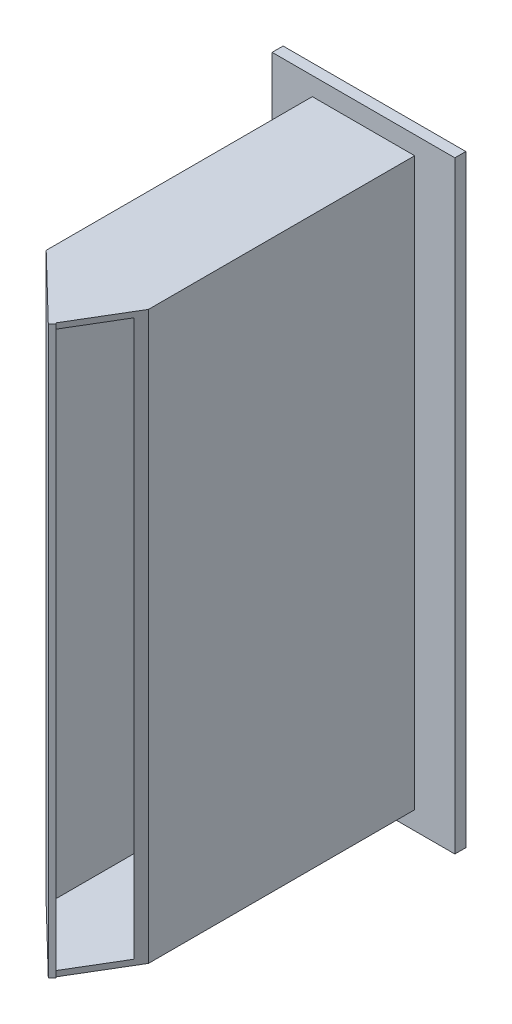
SolidWorks part; units mm, degrees
ref_plane "前视基准面" through (0, 0, 0) normal (0, 0, 1) x (1, 0, 0)
ref_plane "上视基准面" through (0, 0, 0) normal (0, 1, 0) x (1, 0, 0)
ref_plane "右视基准面" through (0, 0, 0) normal (1, 0, 0) x (0, 0, -1)
sketch "草图1" plane through (0, 0, 0) normal (0, 0, 1) x (1, 0, 0)
  line L0 (0, 16.5) -> (10, 16.5) construction
  line L1 (0, 0) -> (10, 0)
  line L2 (0, 0) -> (0, 33)
  line L3 (0, 33) -> (10, 33)
  line L4 (10, 0) -> (10, 33)
  line L5 (2.5, 31.7) -> (7.5, 31.7)
  line L6 (2.5, 31.7) -> (2.5, 1.3)
  line L7 (2.5, 1.3) -> (7.5, 1.3)
  line L8 (7.5, 31.7) -> (7.5, 1.3)
  line L9 (5, 33) -> (5, 0) construction
  dimension "D1" = 33
  dimension "D2" = 10
  dimension "D3" = 5
  dimension "D4" = 30.4
extrude "凸台-拉伸1" add sketch "草图1" along normal blind 0.6
sketch "草图2" plane through (0, 0, 0.6) normal (0, 0, 1) x (1, 0, 0)
  line L0 (7.5, 1.3) -> (7.5, 31.7) construction
  line L1 (2.2, 32) -> (7.8, 32)
  line L2 (2.2, 32) -> (2.2, 1)
  line L3 (2.2, 1) -> (7.8, 1)
  line L4 (7.8, 32) -> (7.8, 1)
  line L5 (2.5, 31.7) -> (2.5, 1.3) construction
  line L6 (7.5, 31.7) -> (2.5, 31.7) construction
  line L7 (2.5, 1.3) -> (7.5, 1.3) construction
  line L9 (2.5, 31.7) -> (7.5, 31.7)
  line L10 (2.5, 31.7) -> (2.5, 1.3)
  line L11 (2.5, 1.3) -> (7.5, 1.3)
  line L12 (7.5, 31.7) -> (7.5, 1.3)
  dimension "D1" = 0.3
  dimension "D2" = 0.3
  dimension "D3" = 0.3
  dimension "D4" = 0.3
extrude "凸台-拉伸2" add sketch "草图2" along normal blind 18
sketch "草图5" plane through (0, 32, 0) normal (0, 1, 0) x (1, 0, 0)
  line L0 (2.2, -15.1659) -> (5.749, -18.6)
  line L1 (2.2, -18.6) -> (2.2, -0.6) construction
  line L2 (7.8, -18.6) -> (2.2, -18.6) construction
  line L3 (5.749, -18.6) -> (7.8, -15.1659)
  line L4 (7.8, -18.6) -> (7.8, -0.6) construction
  line L5 (2.2, -15.1659) -> (2.2, -19.3766)
  line L6 (2.2, -19.3766) -> (7.8, -19.3766)
  line L7 (7.8, -19.3766) -> (7.8, -15.1659)
  dimension "D1" = 4
extrude "切除-拉伸1" cut sketch "草图5" against normal through all
sketch "草图6" plane through (-6.515, 0, 6.7329) normal (-0.6954, 0, 0.7186) x (0.7186, 0, 0.6954)
  line L1 (12.1271, 32) -> (17.0656, 32)
  line L2 (12.1271, 32) -> (12.1271, 1)
  line L3 (12.1271, 1) -> (17.0656, 1)
  line L4 (17.0656, 32) -> (17.0656, 1)
extrude "凸台-拉伸5" add sketch "草图6" against normal blind 0.3
